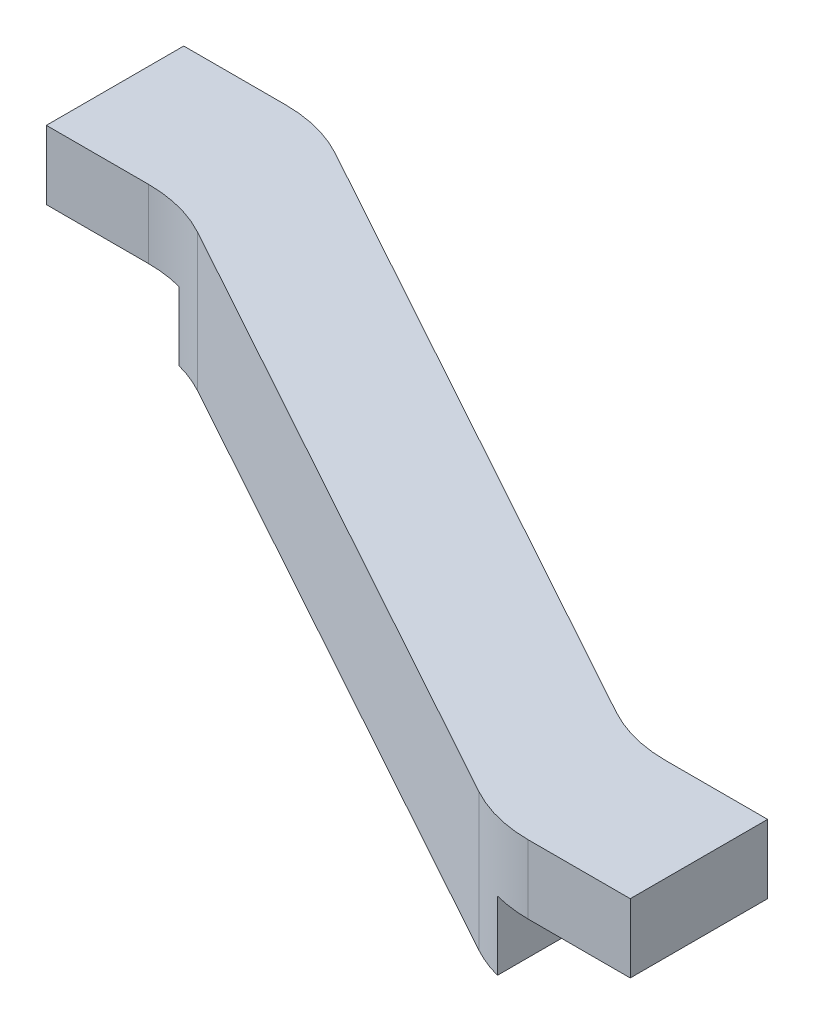
SolidWorks part; units mm, degrees
ref_plane "Alzado" through (0, 0, 0) normal (0, 0, 1) x (1, 0, 0)
ref_plane "Planta" through (0, 0, 0) normal (0, 1, 0) x (1, 0, 0)
ref_plane "Vista lateral" through (0, 0, 0) normal (1, 0, 0) x (0, 0, -1)
sketch "Croquis1" plane through (0, 0, 0) normal (0, 1, 0) x (1, 0, 0)
  line L0 (-70, 0) -> (70, 0) construction
  line L1 (-70, 0) -> (-50, 0)
  line L2 (-50, 0) -> (50, -55)
  line L3 (50, -55) -> (70, -55)
  line L4 (70, -55) -> (70, -75)
  line L5 (70, -75) -> (50, -75)
  line L6 (50, -75) -> (-50, -20)
  line L7 (-50, -20) -> (-70, -20)
  line L8 (-70, -20) -> (-70, 0)
  point P0 (-70, -10)
  point P4 (0, 0)
  point P13 (70, -65)
  dimension "D1" = 140
  dimension "D2" = 20
  dimension "D3" = 20
  dimension "D4" = 55
extrude "Saliente-Extruir1" add sketch "Croquis1" along normal blind 20
fillet "Redondeo1" radius 20 4 edges at (50, 10, 75) (50, 10, 55) (-50, 10, 0) (-50, 10, 20)
sketch "Croquis3" plane through (0, 0, 0) normal (0, 1, 0) x (1, 0, 0)
  line L0 (-70, 0) -> (-50, 0)
  line L1 (-50, 0) -> (-50, -22.7369)
  line L2 (-50, -22.7369) -> (-70, -22.7369)
  line L3 (-70, -22.7369) -> (-70, 0)
  line L4 (-55.1371, 0) -> (-70, 0) construction
  line L5 (70, -52.5479) -> (50, -52.5479)
  line L6 (50, -52.5479) -> (50, -75)
  line L7 (50, -75) -> (70, -75)
  line L8 (70, -75) -> (70, -52.5479)
  line L9 (55.1371, -75) -> (70, -75) construction
  dimension "D1" = 20
  dimension "D2" = 20
extrude "Cortar-Extruir2" cut sketch "Croquis3" along normal blind 10
